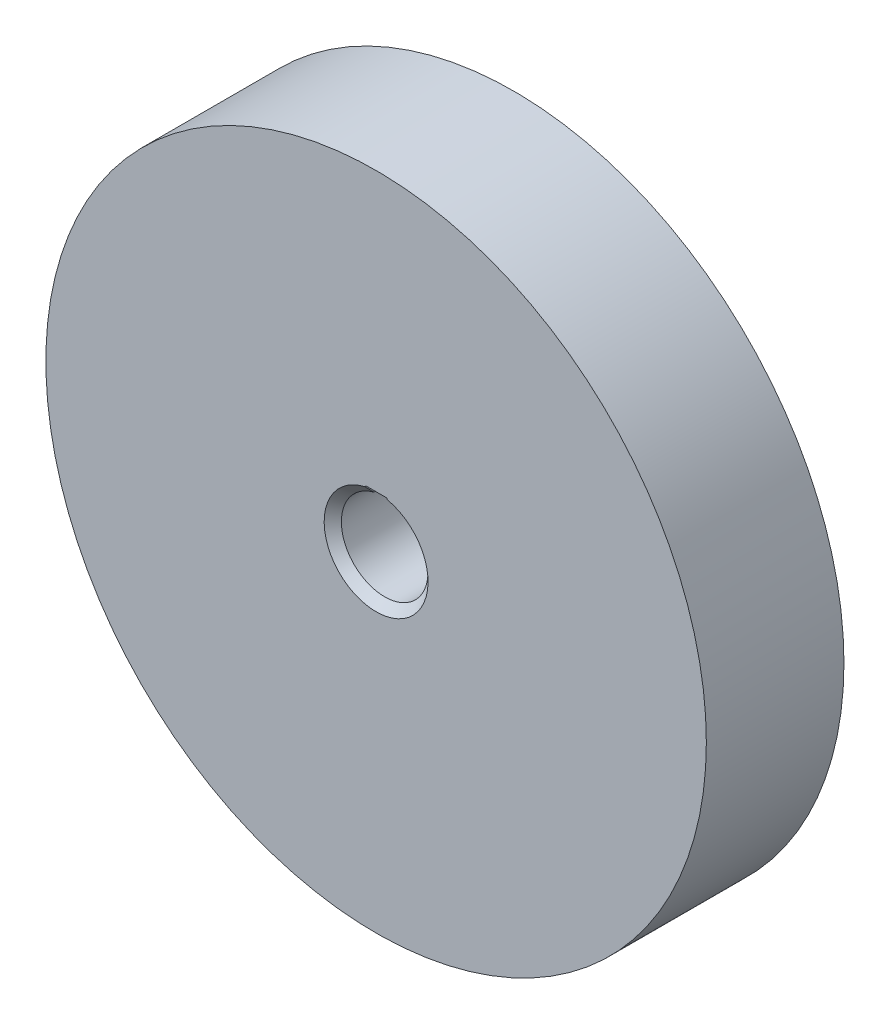
SolidWorks part; units mm, degrees
material "6061-T6 (SS)"
ref_plane "Front Plane" through (0, 0, 0) normal (0, 0, 1) x (1, 0, 0)
ref_plane "Top Plane" through (0, 0, 0) normal (0, 1, 0) x (1, 0, 0)
ref_plane "Right Plane" through (0, 0, 0) normal (1, 0, 0) x (0, 0, -1)
sketch "Sketch1" plane through (0, 0, 0) normal (0, 0, 1) x (1, 0, 0)
  circle A0 centre (0, 0) radius 30.48
  circle A1 centre (0, 0) radius 4
  dimension "D1" = 60.96
  dimension "D2" = 8
extrude "Extrude1" add sketch "Sketch1" along normal mid plane 12.7
sketch "Sketch2" plane through (0, 0, 0) normal (1, 0, 0) x (0, 0, -1)
  line L0 (-4.7625, 19.05) -> (4.7625, 19.05)
  line L2 (4.7625, 19.05) -> (2.4513, 12.7)
  line L3 (2.4513, 12.7) -> (-2.4513, 12.7)
  line L4 (-2.4513, 12.7) -> (-4.7625, 19.05)
  line L5 (-6.35, 0) -> (6.35, 0) construction
  line L6 (-6.35, 30.48) -> (-6.35, -30.48) construction
  line L7 (6.35, -30.48) -> (6.35, 30.48) construction
  point P2 (0, 19.05)
  point P5 (0, 12.7)
  dimension "D1" = 19.05
  dimension "D2" = 6.35
  dimension "D3" = 9.525
  dimension "D4" = 40
chamfer "Chamfer1" distance 0.7937 angle 45 2 edges at (4, 0, -6.35) (4, 0, 6.35)
sketch "Sketch3" plane through (0, 0, 6.35) normal (0, 0, 1) x (1, 0, 0)
  line L0 (0, 0) -> (0, 3.8) construction
  line L2 (-1, 4.8) -> (1, 4.8)
  line L3 (-1, 4.8) -> (-1, 2.8)
  line L4 (-1, 2.8) -> (1, 2.8)
  line L5 (1, 4.8) -> (1, 2.8)
  line L6 (-1, 4.8) -> (1, 2.8) construction
  line L7 (-1, 2.8) -> (1, 4.8) construction
  dimension "D1" = 2.8
  dimension "D2" = 2
  dimension "D3" = 2
extrude "Cut-Extrude1" cut sketch "Sketch3" against normal through all contours L4 L5 L2 L3
